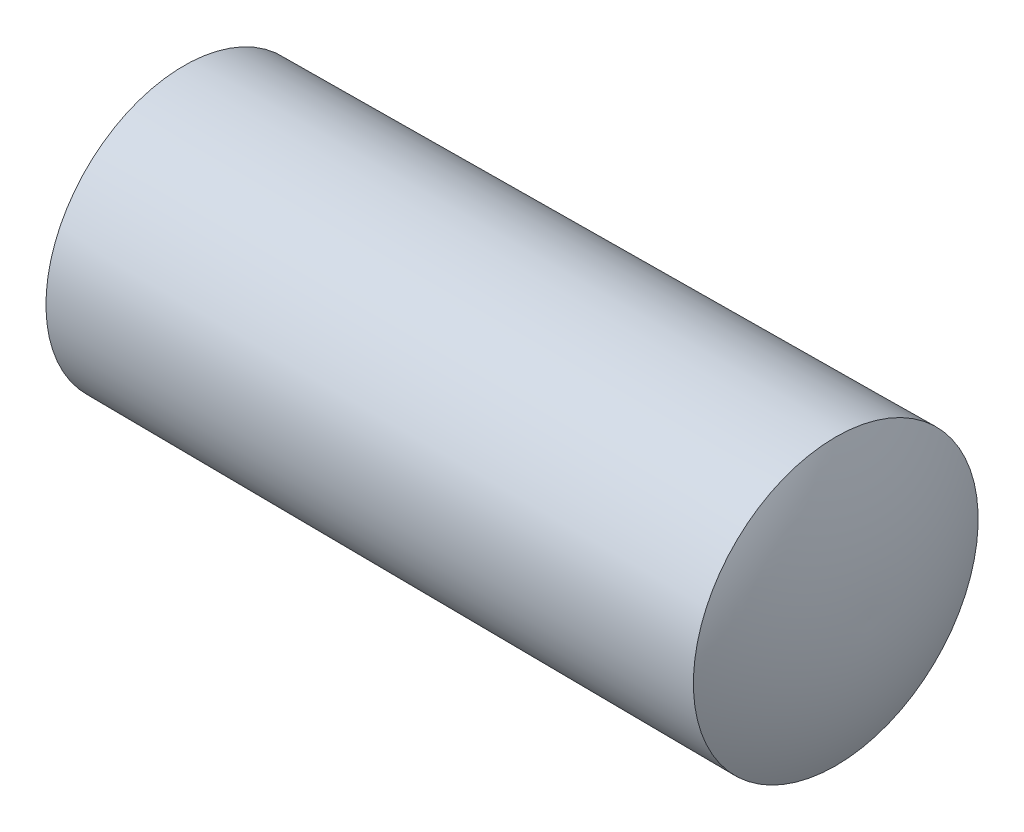
SolidWorks part; units mm, degrees
ref_plane "前视" through (0, 0, 0) normal (0, 0, 1) x (1, 0, 0)
ref_plane "上视" through (0, 0, 0) normal (0, 1, 0) x (1, 0, 0)
ref_plane "右视" through (0, 0, 0) normal (1, 0, 0) x (0, 0, -1)
sketch "草图1" plane through (0, 0, 0) normal (0, 0, 1) x (1, 0, 0)
  line L0 (1.2, 5) -> (24.8, 5.156) construction
  line L1 (0, 0) -> (26, 0)
  line L2 (0, 0) -> (1.2454, 0) construction
  line L6 (1.2, -5) -> (24.8, -5.156)
  arc A0 (26, 0) -> (24.8, -5.156) centre (15.3747, -0.2447) cw
  arc A1 (0, 0) -> (1.2, -5) centre (9.997, -0.2447) ccw
  dimension "r2" = 10.6282
  dimension "D3" = 1.2
  dimension "r1" = 10
  dimension "l" = 26
  dimension "a" = 1.2
  dimension "d" = 10
revolve "基体-旋转" add sketch "草图1" angle 360 about L2
